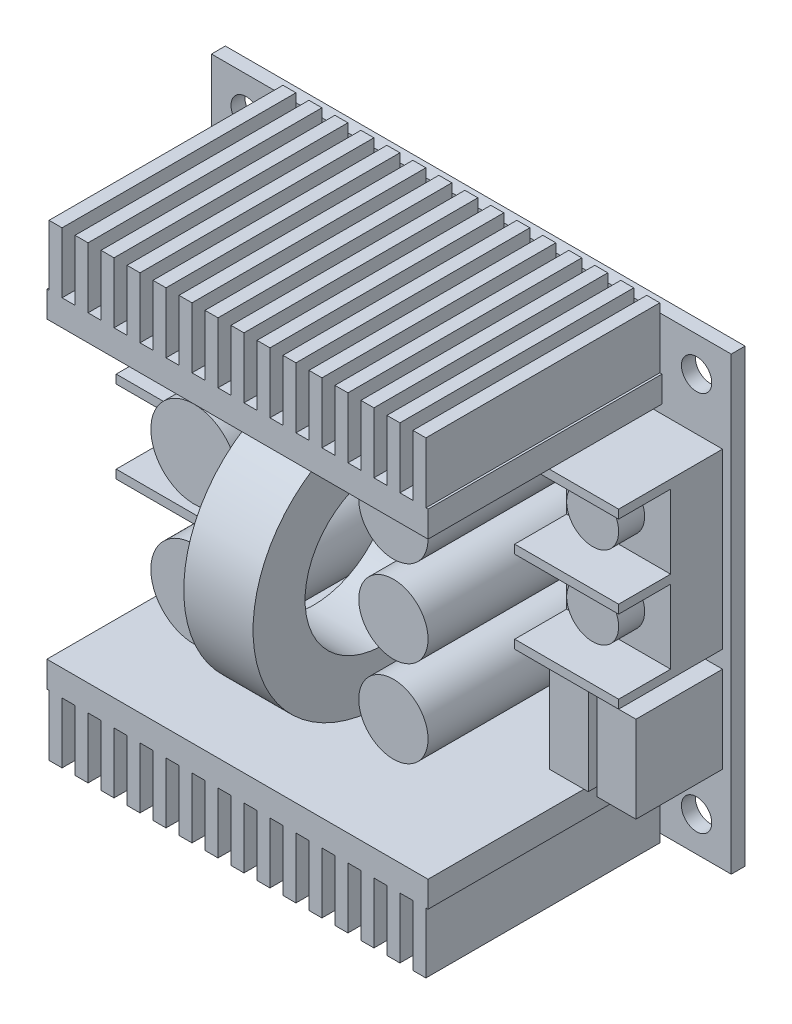
SolidWorks part; units mm, degrees
ref_plane "Top Plane" through (0, 0, 0) normal (0, 0, 1) x (1, 0, 0)
ref_plane "Right Plane" through (0, 0, 0) normal (0, 1, 0) x (1, 0, 0)
ref_plane "Front Plane" through (0, 0, 0) normal (1, 0, 0) x (0, 0, -1)
sketch "Sketch1" plane through (0, 0, 0) normal (0, 0, 1) x (1, 0, 0)
  line L0 (-30, 26) -> (30, -26) construction
  line L1 (-30, 26) -> (30, 26)
  line L2 (-30, 26) -> (-30, -26)
  line L3 (-30, -26) -> (30, -26)
  line L4 (30, 26) -> (30, -26)
  dimension "D1" = 60
  dimension "D2" = 52
extrude "Boss-Extrude1" add sketch "Sketch1" along normal mid plane 1.6
sketch "Sketch2" plane through (0, 0, 0.8) normal (0, 0, 1) x (1, 0, 0)
  line L0 (-30, 0) -> (30, 0) construction
  line L1 (-22, -27) -> (22, -27)
  line L2 (-22, -27) -> (-22, -17)
  line L3 (-22, -17) -> (22, -17)
  line L4 (22, -27) -> (22, -17)
  line L5 (-30, 26) -> (-30, -26) construction
  line L6 (30, -26) -> (30, 26) construction
  line L7 (22, 27) -> (22, 17)
  line L8 (-22, 17) -> (22, 17)
  line L9 (-22, 27) -> (-22, 17)
  line L10 (-22, 27) -> (22, 27)
  line L11 (0, -27) -> (0, 27) construction
  line L12 (-30, -26) -> (30, -26) construction
  dimension "D1" = 10
  dimension "D2" = 1
  dimension "D3" = 8
extrude "Boss-Extrude2" add sketch "Sketch2" along normal blind 27
sketch "Sketch3" plane through (0, 0, 27.8) normal (0, 0, 1) x (1, 0, 0)
  line L0 (-22, -27) -> (22, -27) construction
  line L1 (-23.25, -20) -> (-21.75, -20)
  line L2 (-23.25, -20) -> (-23.25, -27)
  line L3 (-23.25, -27) -> (-21.75, -27)
  line L4 (-21.75, -20) -> (-21.75, -27)
  line L5 (-20.25, -20) -> (-18.75, -20)
  line L6 (-20.25, -20) -> (-20.25, -27)
  line L7 (-20.25, -27) -> (-18.75, -27)
  line L8 (-18.75, -20) -> (-18.75, -27)
  line L9 (-17.25, -20) -> (-15.75, -20)
  line L10 (-17.25, -20) -> (-17.25, -27)
  line L11 (-17.25, -27) -> (-15.75, -27)
  line L12 (-15.75, -20) -> (-15.75, -27)
  line L13 (-14.25, -20) -> (-12.75, -20)
  line L14 (-14.25, -20) -> (-14.25, -27)
  line L15 (-14.25, -27) -> (-12.75, -27)
  line L16 (-12.75, -20) -> (-12.75, -27)
  line L17 (-11.25, -20) -> (-9.75, -20)
  line L18 (-11.25, -20) -> (-11.25, -27)
  line L19 (-11.25, -27) -> (-9.75, -27)
  line L20 (-9.75, -20) -> (-9.75, -27)
  line L21 (-8.25, -20) -> (-6.75, -20)
  line L22 (-8.25, -20) -> (-8.25, -27)
  line L23 (-8.25, -27) -> (-6.75, -27)
  line L24 (-6.75, -20) -> (-6.75, -27)
  line L25 (-5.25, -20) -> (-3.75, -20)
  line L26 (-5.25, -20) -> (-5.25, -27)
  line L27 (-5.25, -27) -> (-3.75, -27)
  line L28 (-3.75, -20) -> (-3.75, -27)
  line L29 (-2.25, -20) -> (-0.75, -20)
  line L30 (-2.25, -20) -> (-2.25, -27)
  line L31 (-2.25, -27) -> (-0.75, -27)
  line L32 (-0.75, -20) -> (-0.75, -27)
  line L33 (0.75, -20) -> (2.25, -20)
  line L34 (0.75, -20) -> (0.75, -27)
  line L35 (0.75, -27) -> (2.25, -27)
  line L36 (2.25, -20) -> (2.25, -27)
  line L37 (3.75, -20) -> (5.25, -20)
  line L38 (3.75, -20) -> (3.75, -27)
  line L39 (3.75, -27) -> (5.25, -27)
  line L40 (5.25, -20) -> (5.25, -27)
  line L41 (6.75, -20) -> (8.25, -20)
  line L42 (6.75, -20) -> (6.75, -27)
  line L43 (6.75, -27) -> (8.25, -27)
  line L44 (8.25, -20) -> (8.25, -27)
  line L45 (9.75, -20) -> (11.25, -20)
  line L46 (9.75, -20) -> (9.75, -27)
  line L47 (9.75, -27) -> (11.25, -27)
  line L48 (11.25, -20) -> (11.25, -27)
  line L49 (12.75, -20) -> (14.25, -20)
  line L50 (12.75, -20) -> (12.75, -27)
  line L51 (12.75, -27) -> (14.25, -27)
  line L52 (14.25, -20) -> (14.25, -27)
  line L53 (15.75, -20) -> (17.25, -20)
  line L54 (15.75, -20) -> (15.75, -27)
  line L55 (15.75, -27) -> (17.25, -27)
  line L56 (17.25, -20) -> (17.25, -27)
  line L57 (18.75, -20) -> (20.25, -20)
  line L58 (18.75, -20) -> (18.75, -27)
  line L59 (18.75, -27) -> (20.25, -27)
  line L60 (20.25, -20) -> (20.25, -27)
  line L61 (21.75, -20) -> (23.25, -20)
  line L62 (21.75, -20) -> (21.75, -27)
  line L63 (21.75, -27) -> (23.25, -27)
  line L64 (23.25, -20) -> (23.25, -27)
  line L65 (-23.25, -20) -> (-20.25, -20) construction
  line L66 (-22, -22.7057) -> (-23.25, -22.7057) construction
  line L67 (-22, -17) -> (-22, -26) construction
  line L68 (23.25, -22.7057) -> (22, -22.7057) construction
  line L69 (22, -27) -> (22, -17) construction
  line L70 (22, -17) -> (-22, -17) construction
  line L71 (-38.482, 0) -> (38.482, 0) construction
  line L72 (23.25, 20) -> (23.25, 27)
  line L73 (21.75, 27) -> (23.25, 27)
  line L74 (21.75, 20) -> (21.75, 27)
  line L75 (21.75, 20) -> (23.25, 20)
  line L76 (20.25, 20) -> (20.25, 27)
  line L77 (18.75, 27) -> (20.25, 27)
  line L78 (18.75, 20) -> (18.75, 27)
  line L79 (18.75, 20) -> (20.25, 20)
  line L80 (17.25, 20) -> (17.25, 27)
  line L81 (15.75, 27) -> (17.25, 27)
  line L82 (15.75, 20) -> (15.75, 27)
  line L83 (15.75, 20) -> (17.25, 20)
  line L84 (14.25, 20) -> (14.25, 27)
  line L85 (12.75, 27) -> (14.25, 27)
  line L86 (12.75, 20) -> (12.75, 27)
  line L87 (12.75, 20) -> (14.25, 20)
  line L88 (11.25, 20) -> (11.25, 27)
  line L89 (9.75, 27) -> (11.25, 27)
  line L90 (9.75, 20) -> (9.75, 27)
  line L91 (9.75, 20) -> (11.25, 20)
  line L92 (8.25, 20) -> (8.25, 27)
  line L93 (6.75, 27) -> (8.25, 27)
  line L94 (6.75, 20) -> (6.75, 27)
  line L95 (6.75, 20) -> (8.25, 20)
  line L96 (5.25, 20) -> (5.25, 27)
  line L97 (3.75, 27) -> (5.25, 27)
  line L98 (3.75, 20) -> (3.75, 27)
  line L99 (3.75, 20) -> (5.25, 20)
  line L100 (2.25, 20) -> (2.25, 27)
  line L101 (0.75, 27) -> (2.25, 27)
  line L102 (0.75, 20) -> (0.75, 27)
  line L103 (0.75, 20) -> (2.25, 20)
  line L104 (-0.75, 20) -> (-0.75, 27)
  line L105 (-2.25, 27) -> (-0.75, 27)
  line L106 (-2.25, 20) -> (-2.25, 27)
  line L107 (-2.25, 20) -> (-0.75, 20)
  line L108 (-3.75, 20) -> (-3.75, 27)
  line L109 (-5.25, 27) -> (-3.75, 27)
  line L110 (-5.25, 20) -> (-5.25, 27)
  line L111 (-5.25, 20) -> (-3.75, 20)
  line L112 (-6.75, 20) -> (-6.75, 27)
  line L113 (-8.25, 27) -> (-6.75, 27)
  line L114 (-8.25, 20) -> (-8.25, 27)
  line L115 (-8.25, 20) -> (-6.75, 20)
  line L116 (-9.75, 20) -> (-9.75, 27)
  line L117 (-11.25, 27) -> (-9.75, 27)
  line L118 (-11.25, 20) -> (-11.25, 27)
  line L119 (-11.25, 20) -> (-9.75, 20)
  line L120 (-12.75, 20) -> (-12.75, 27)
  line L121 (-14.25, 27) -> (-12.75, 27)
  line L122 (-14.25, 20) -> (-14.25, 27)
  line L123 (-14.25, 20) -> (-12.75, 20)
  line L124 (-15.75, 20) -> (-15.75, 27)
  line L125 (-17.25, 27) -> (-15.75, 27)
  line L126 (-17.25, 20) -> (-17.25, 27)
  line L127 (-17.25, 20) -> (-15.75, 20)
  line L128 (-18.75, 20) -> (-18.75, 27)
  line L129 (-20.25, 27) -> (-18.75, 27)
  line L130 (-20.25, 20) -> (-20.25, 27)
  line L131 (-20.25, 20) -> (-18.75, 20)
  line L132 (-21.75, 20) -> (-21.75, 27)
  line L133 (-23.25, 27) -> (-21.75, 27)
  line L134 (-23.25, 20) -> (-23.25, 27)
  line L135 (-23.25, 20) -> (-21.75, 20)
  dimension "D1" = 16
  dimension "D2" = 3
  dimension "D3" = 1.5
  dimension "D4" = 3
extrude "Cut-Extrude1" cut sketch "Sketch3" against normal up to surface (27 mm away) up to face at (0, 0, 0.8)
sketch "Sketch4" plane through (0, 0, 0.8) normal (0, 0, 1) x (1, 0, 0)
  line L0 (-30, 0) -> (30, 0) construction
  line L1 (-30, 26) -> (-30, -26) construction
  line L2 (30, -26) -> (30, 26) construction
  line L3 (0, -30.646) -> (0, 35.9865) construction
  circle A0 centre (-26, -22) radius 1.75
  circle A1 centre (-26, 22) radius 1.75
  circle A2 centre (26, 22) radius 1.75
  circle A3 centre (26, -22) radius 1.75
  dimension "D1" = 44
  dimension "D3" = 3.5
  dimension "D2" = 52
extrude "Cut-Extrude2" cut sketch "Sketch4" against normal through all
sketch "Sketch5" plane through (0, 0, 0.8) normal (0, 0, 1) x (1, 0, 0)
  line L0 (24, -1.5528) -> (24, -15.2326) construction
  line L1 (19, -6) -> (23.5, -6)
  line L2 (19, -6) -> (19, -16)
  line L3 (19, -16) -> (23.5, -16)
  line L4 (23.5, -6) -> (23.5, -16)
  line L5 (24.5, -6) -> (24.5, -16)
  line L6 (29, -16) -> (24.5, -16)
  line L7 (29, -6) -> (29, -16)
  line L8 (29, -6) -> (24.5, -6)
  line L9 (30, -26) -> (30, 26) construction
  line L10 (22, -17) -> (-22, -17) construction
  dimension "D1" = 1
  dimension "D2" = 10
  dimension "D3" = 10
  dimension "D4" = 1
  dimension "D5" = 1
extrude "Boss-Extrude3" add sketch "Sketch5" along normal blind 10
sketch "Sketch6" plane through (0, 0, 0.8) normal (0, 0, 1) x (1, 0, 0)
  line L0 (30, -26) -> (30, 26) construction
  line L1 (17, 16) -> (29, 16)
  line L2 (17, 16) -> (17, -4)
  line L3 (17, -4) -> (29, -4)
  line L4 (29, 16) -> (29, -4)
  line L5 (29, -6) -> (24.5, -6) construction
  line L6 (-22, 17) -> (22, 17) construction
  line L7 (-30, 0) -> (-17, 0) construction
  line L8 (-29, -10) -> (-17, -10)
  line L9 (-29, -10) -> (-29, 10)
  line L10 (-29, 10) -> (-17, 10)
  line L11 (-17, -10) -> (-17, 10)
  line L12 (-30, 26) -> (-30, -26) construction
  dimension "D1" = 1
  dimension "D2" = 2
  dimension "D3" = 1
  dimension "D4" = 12
  dimension "D5" = 1
extrude "Boss-Extrude4" add sketch "Sketch6" along normal blind 12
sketch "Sketch7" plane through (0, 0, 12.8) normal (0, 0, 1) x (1, 0, 0)
  line L0 (17, 16) -> (17, -4) construction
  line L1 (17, 15) -> (29, 15)
  line L2 (17, 15) -> (17, 6.5)
  line L3 (17, 6.5) -> (29, 6.5)
  line L4 (29, 15) -> (29, 6.5)
  line L5 (29, -4) -> (29, 16) construction
  line L6 (17, 6) -> (29, 6) construction
  line L7 (17, 16) -> (17, -4) construction
  line L8 (29, -4) -> (29, 16) construction
  line L9 (29, -3) -> (29, 5.5)
  line L10 (17, 5.5) -> (29, 5.5)
  line L11 (17, -3) -> (17, 5.5)
  line L12 (17, -3) -> (29, -3)
  line L13 (17, -4) -> (29, -4) construction
  line L14 (-29, 9) -> (-17, 9)
  line L15 (-29, 9) -> (-29, 0.5)
  line L16 (-29, 0.5) -> (-17, 0.5)
  line L17 (-17, 9) -> (-17, 0.5)
  line L18 (-29, 0) -> (-17, 0) construction
  line L19 (-17, -9) -> (-17, -0.5)
  line L20 (-29, -0.5) -> (-17, -0.5)
  line L21 (-29, -9) -> (-29, -0.5)
  line L22 (-29, -9) -> (-17, -9)
  line L23 (-29, 10) -> (-29, -10) construction
  line L24 (-17, -10) -> (-17, 10) construction
  point P30 (-29, 0)
  point P33 (-17, 0)
  dimension "D1" = 1
  dimension "D2" = 1
  dimension "D3" = 1
extrude "Cut-Extrude3" cut sketch "Sketch7" against normal offset from surface (6 mm away) 6 up to face at (-27.75, 22, 0.8)
sketch "Sketch8" plane through (0, 0, 6.8) normal (0, 0, 1) x (1, 0, 0)
  line L0 (17, 10.75) -> (29, 10.75) construction
  line L1 (17, 6.5) -> (17, 15) construction
  line L2 (29, 15) -> (29, 6.5) construction
  line L3 (17, 1.25) -> (29, 1.25) construction
  line L4 (17, -3) -> (17, 5.5) construction
  line L5 (29, 5.5) -> (29, -3) construction
  line L6 (-29, 4.75) -> (-17, 4.75) construction
  line L7 (-29, -4.75) -> (-17, -4.75) construction
  line L8 (-29, -9) -> (-29, -0.5) construction
  line L9 (-17, -10) -> (-17, 10) construction
  line L10 (-29, 0.5) -> (-29, 9) construction
  line L11 (-17, 9) -> (-17, 0.5) construction
  circle A0 centre (23, 10.75) radius 3
  circle A1 centre (23, 1.25) radius 3
  circle A2 centre (-23, 4.75) radius 3
  circle A3 centre (-23, -4.75) radius 3
  point P24 (-29, -4.75)
  point P27 (-17, -4.75)
  point P30 (-29, 4.75)
  point P33 (-17, 4.75)
  dimension "D1" = 6
extrude "Boss-Extrude5" add sketch "Sketch8" along normal blind 3
sketch "Sketch9" plane through (0, 0, 0.8) normal (0, 0, 1) x (1, 0, 0)
  line L0 (-31.7963, 0) -> (33.7681, 0) construction
  line L1 (22, -17) -> (-22, -17) construction
  circle A0 centre (11, 0) radius 4
  circle A1 centre (11, -10) radius 4
  circle A2 centre (11, 10) radius 4
  point P7 (8.7912, -9.5307)
  point P10 (10.5005, -10.0349)
  dimension "D1" = 8
  dimension "D2" = 7
  dimension "D3" = 11
extrude "Boss-Extrude6" add sketch "Sketch9" along normal blind 20
sketch "Sketch10" plane through (0, 0, 0.8) normal (0, 0, 1) x (1, 0, 0)
  line L0 (-34.1614, 0) -> (43.5559, 0) construction
  circle A0 centre (-10, 7) radius 5
  circle A1 centre (-10, -7) radius 5
  point P7 (-9.9086, 7.7642)
  dimension "D1" = 10
  dimension "D2" = 10
  dimension "D3" = 14
extrude "Boss-Extrude7" add sketch "Sketch10" along normal blind 22
sketch "Sketch11" plane through (0, 0, 0) normal (1, 0, 0) x (0, 0, -1)
  line L0 (-15, 0) -> (0, 0) construction
  circle A0 centre (-15, 0) radius 15
  circle A1 centre (-15, 0) radius 9
  dimension "D1" = 30
  dimension "D2" = 6
extrude "Boss-Extrude8" add sketch "Sketch11" along normal mid plane 8
